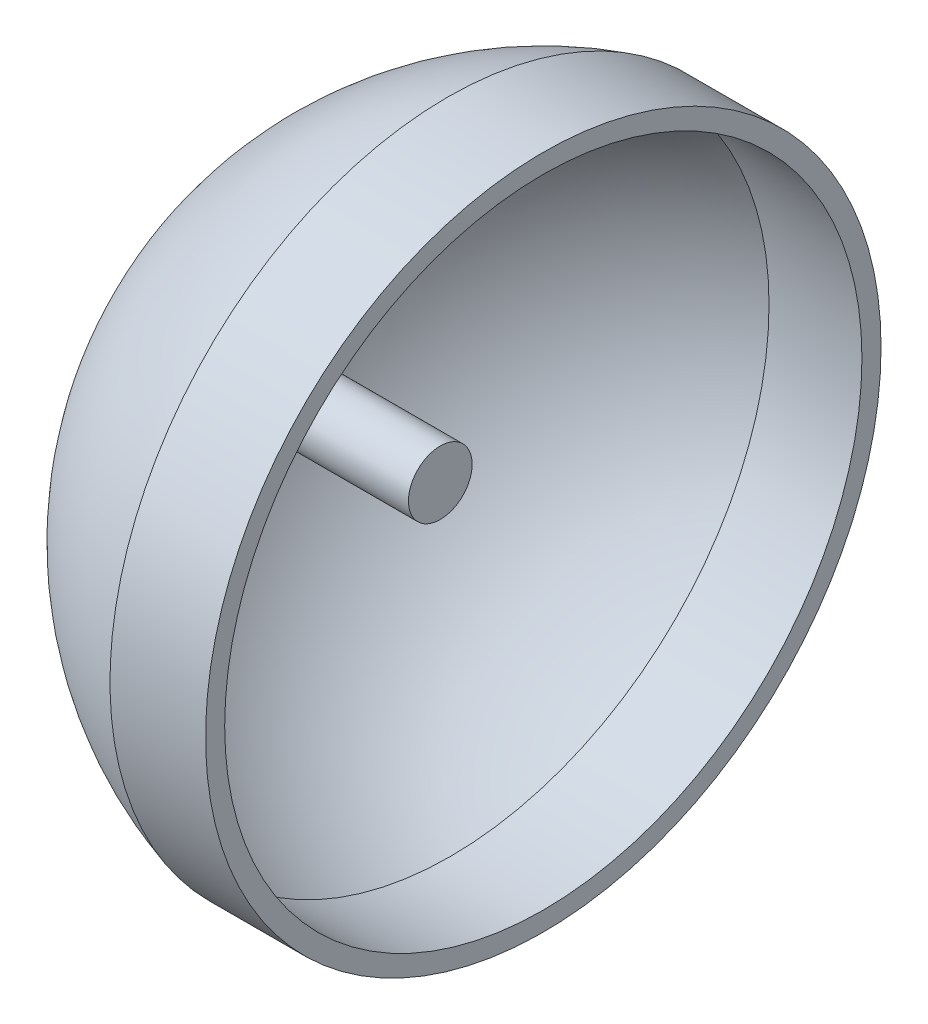
SolidWorks part; units mm, degrees
ref_plane "Front Plane" through (0, 0, 0) normal (0, 0, 1) x (1, 0, 0)
ref_plane "Top Plane" through (0, 0, 0) normal (0, 1, 0) x (1, 0, 0)
ref_plane "Right Plane" through (0, 0, 0) normal (1, 0, 0) x (0, 0, -1)
sketch "Sketch2" plane through (0, 0, 0) normal (0, 0, 1) x (1, 0, 0)
  line L0 (0, 0) -> (0, 53)
  line L1 (0, 53) -> (-15, 53)
  line L2 (0, 0) -> (-71.1386, 0) construction
  line L3 (-49.1664, 0) -> (-49.1664, 10)
  line L4 (-49.1664, 10) -> (-54.1664, 10)
  line L5 (0, 0) -> (-49.1664, 0)
  arc A0 (-15, 53) -> (-54.1664, 10) centre (0, 0) ccw
  dimension "D1" = 15
  dimension "D2" = 53
  dimension "D3" = 10
  dimension "D4" = 5
revolve "Revolve1" add sketch "Sketch2" angle 360 about L2
shell "Shell1" thickness 3
sketch "Sketch3" plane through (-46.1664, 0, 0) normal (1, 0, 0) x (0, 0, -1)
  circle A0 centre (0, 0) radius 5
extrude "Boss-Extrude1" add sketch "Sketch3" along normal blind 30
